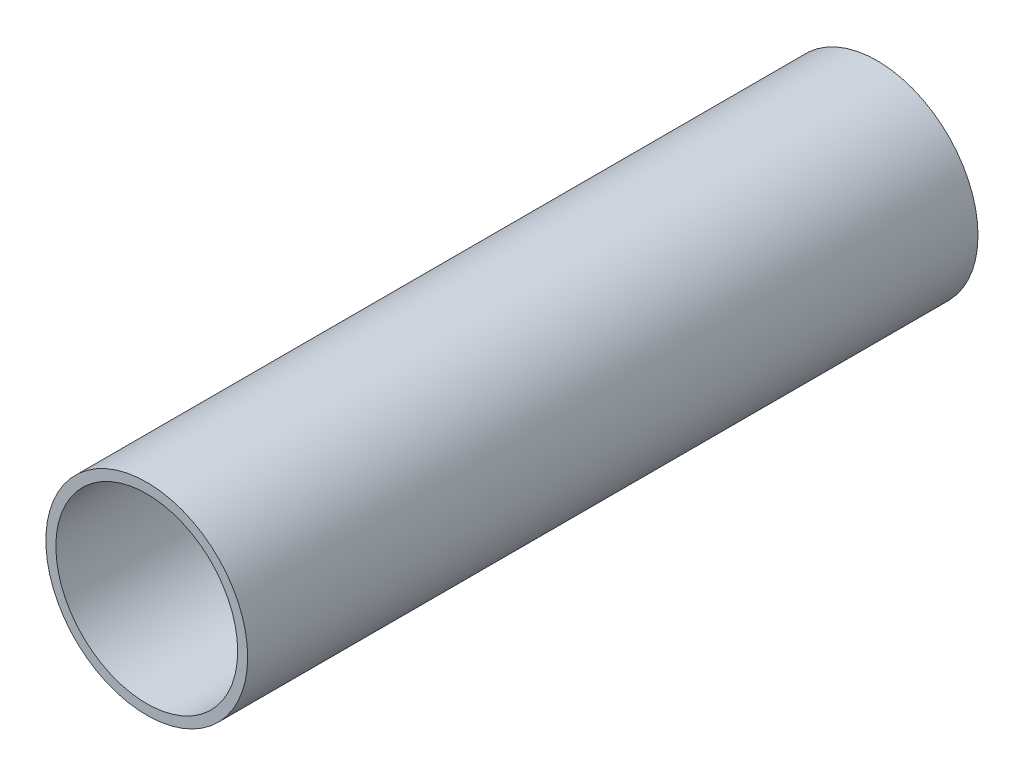
SolidWorks part; units mm, degrees
ref_plane "Front Plane" through (0, 0, 0) normal (0, 0, 1) x (1, 0, 0)
ref_plane "Top Plane" through (0, 0, 0) normal (0, 1, 0) x (1, 0, 0)
ref_plane "Right Plane" through (0, 0, 0) normal (1, 0, 0) x (0, 0, -1)
sketch "Sketch1" plane through (0, 0, 0) normal (0, 0, 1) x (1, 0, 0)
  circle A1 centre (0, 0) radius 84.582
  dimension "D1" = 169.164
extrude "Boss-Extrude1" add sketch "Sketch1" along normal mid plane 612.14
sketch "Sketch2" plane through (0, 0, 306.07) normal (0, 0, 1) x (1, 0, 0)
  circle A0 centre (0, 0) radius 76.2
  dimension "D1" = 152.4
extrude "Cut-Extrude1" cut sketch "Sketch2" against normal up to surface (612.14 mm away) up to face at (84.582, 0, -306.07)
equation "\"FIN_CAN_LENGTH\"=24.1"
equation "\"D1@Boss-Extrude1\"=\"FIN_CAN_LENGTH\""
equation "\"FIN_CAN_OUTER_RADIUS\"= 3.33"
equation "\"FIN_CAN_INNER_RADIUS\"= 3"
equation "\"D1@Sketch1\"=\"FIN_CAN_OUTER_RADIUS\"*2"
equation "\"D1@Sketch2\"=\"FIN_CAN_INNER_RADIUS\"*2"
